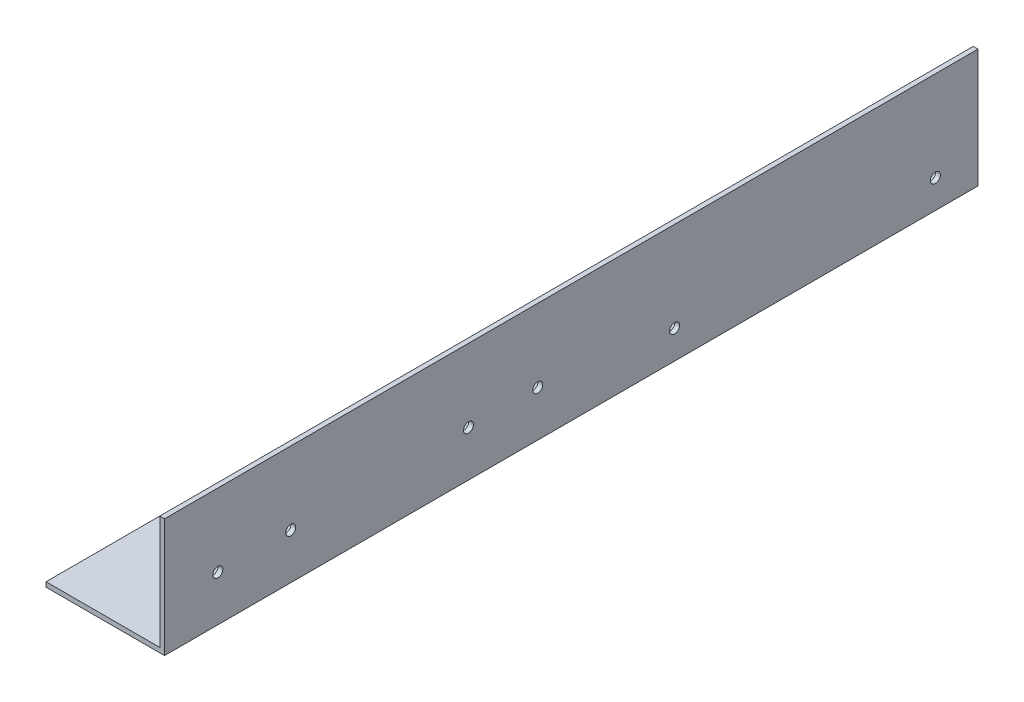
SolidWorks part; units mm, degrees
ref_plane "Front Plane" through (0, 0, 0) normal (0, 0, 1) x (1, 0, 0)
ref_plane "Top Plane" through (0, 0, 0) normal (0, 1, 0) x (1, 0, 0)
ref_plane "Right Plane" through (0, 0, 0) normal (1, 0, 0) x (0, 0, -1)
sketch "Sketch1" plane through (0, 0, 0) normal (0, 0, 1) x (1, 0, 0)
  line L0 (0, 0) -> (-50, 0)
  line L1 (-50, 0) -> (-50, 2)
  line L2 (-50, 2) -> (-2, 2)
  line L3 (-2, 2) -> (-2, 50)
  line L4 (-2, 50) -> (0, 50)
  line L5 (0, 50) -> (0, 0)
  dimension "D1" = 50
  dimension "D2" = 50
  dimension "D3" = 2
  dimension "D4" = 2
extrude "Boss-Extrude1" add sketch "Sketch1" along normal blind 343.25
sketch "Sketch2" plane through (0, 0, 0) normal (1, 0, 0) x (0, 0, -1)
  circle A0 centre (-185.75, 19.25) radius 2.1
  circle A1 centre (-215, 19.25) radius 2.1
  circle A2 centre (-290, 19.25) radius 2.1
  circle A3 centre (-320.75, 19.25) radius 2.1
  dimension "D1" = 4.2
  dimension "D2" = 19.25
  dimension "D3" = 185.75
  dimension "D4" = 215
  dimension "D5" = 290
  dimension "D6" = 320.75
extrude "Cut-Extrude1" cut sketch "Sketch2" against normal mid plane 10
sketch "Sketch3" plane through (0, 0, 0) normal (1, 0, 0) x (0, 0, -1)
  circle A0 centre (-18, 12) radius 2.1
  circle A1 centre (-128, 12) radius 2.1
  dimension "D1" = 4.2
  dimension "D2" = 12
  dimension "D3" = 18
  dimension "D4" = 128
extrude "Cut-Extrude2" cut sketch "Sketch3" against normal mid plane 10
sketch "Sketch4" plane through (0, 0, 0) normal (0, 1, 0) x (1, 0, 0)
  circle A0 centre (-25, -12.5) radius 2.75
  circle A1 centre (-25, -37.5) radius 2.75
  dimension "D1" = 5.5
  dimension "D2" = 25
  dimension "D3" = 12.5
  dimension "D4" = 37.5
extrude "Cut-Extrude3" cut sketch "Sketch4" against normal mid plane 10
